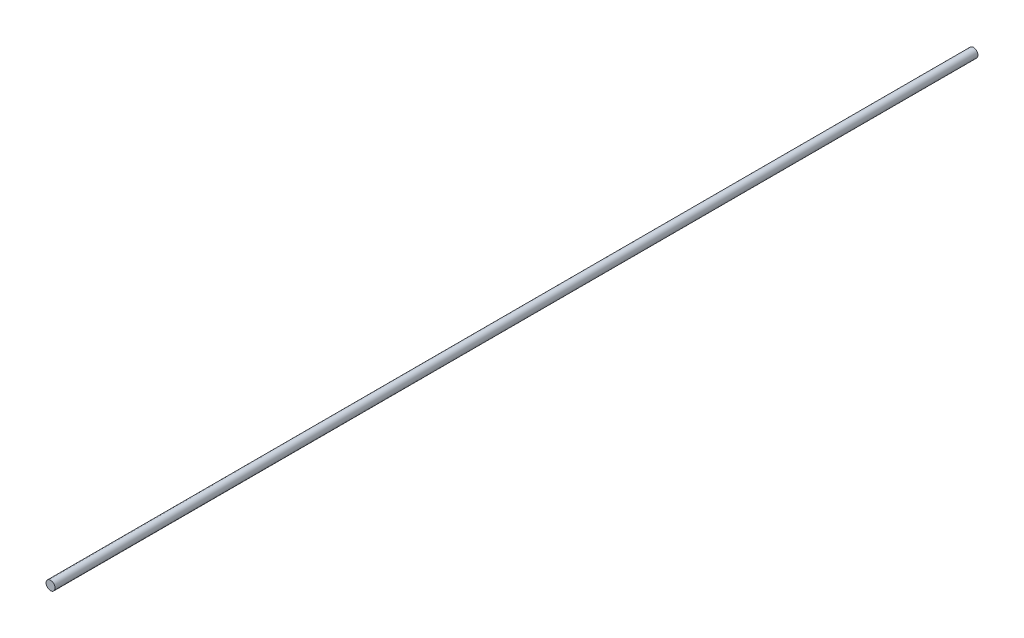
SolidWorks part; units mm, degrees
material "Hexcel AS4C (3000 Filaments)"
ref_plane "Front Plane" through (0, 0, 0) normal (0, 0, 1) x (1, 0, 0)
ref_plane "Top Plane" through (0, 0, 0) normal (0, 1, 0) x (1, 0, 0)
ref_plane "Right Plane" through (0, 0, 0) normal (1, 0, 0) x (0, 0, -1)
sketch "Sketch1" plane through (0, 0, 0) normal (0, 0, 1) x (1, 0, 0)
  circle A0 centre (0, 0) radius 1
  dimension "D1" = 2
extrude "Boss-Extrude1" add sketch "Sketch1" along normal blind 205
